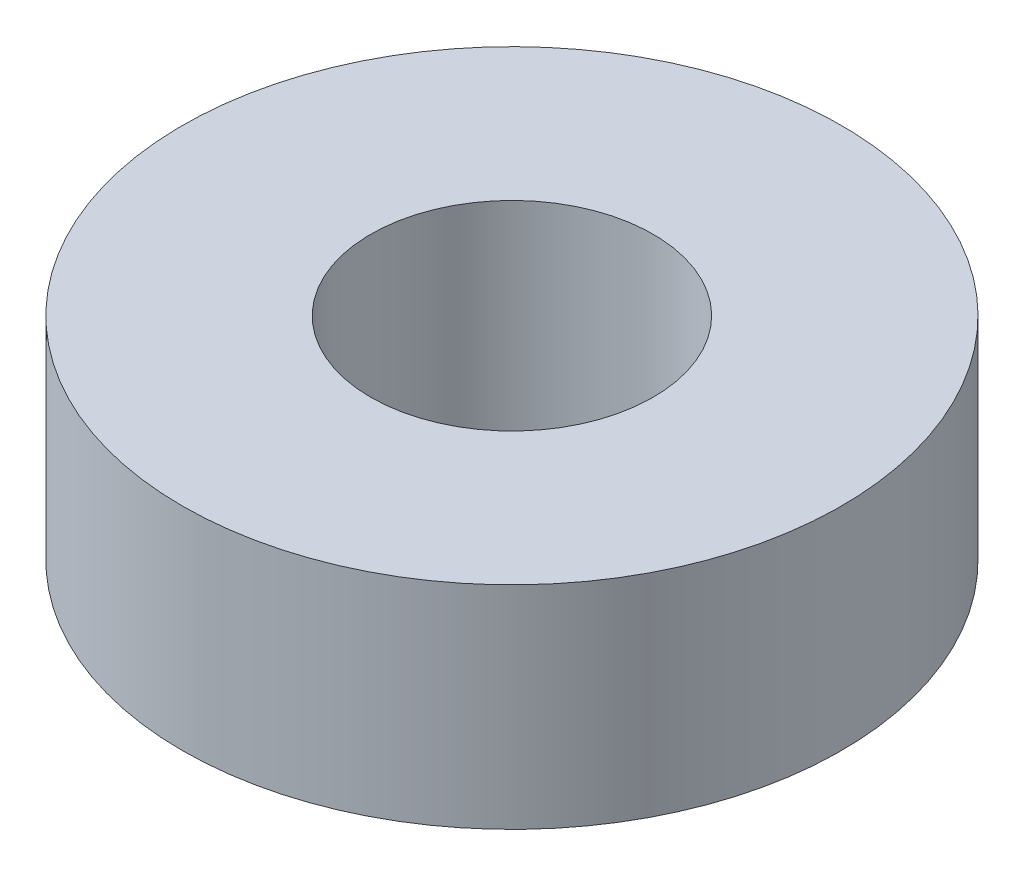
SolidWorks part; units mm, degrees
ref_plane "Front Plane" through (0, 0, 0) normal (0, 0, 1) x (1, 0, 0)
ref_plane "Top Plane" through (0, 0, 0) normal (0, 1, 0) x (1, 0, 0)
ref_plane "Right Plane" through (0, 0, 0) normal (1, 0, 0) x (0, 0, -1)
sketch "Sketch1" plane through (0, 0, 0) normal (0, 1, 0) x (1, 0, 0)
  circle A0 centre (0, 0) radius 4.7625
  circle A1 centre (0, 0) radius 11.1125
  dimension "D1" = 22.225
  dimension "D2" = 9.525
extrude "Boss-Extrude1" add sketch "Sketch1" along normal blind 7.1425
